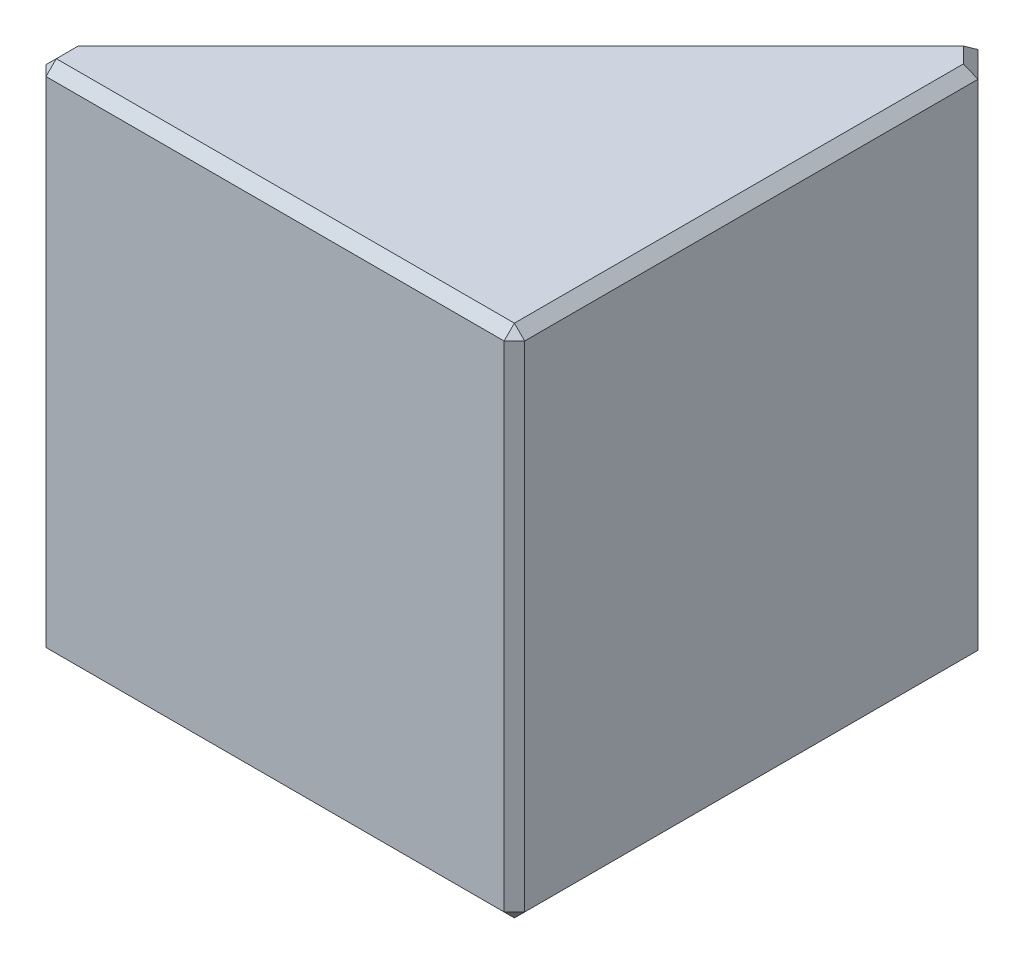
SolidWorks part; units mm, degrees
ref_plane "前视基准面" through (0, 0, 0) normal (0, 0, 1) x (1, 0, 0)
ref_plane "上视基准面" through (0, 0, 0) normal (0, 1, 0) x (1, 0, 0)
ref_plane "右视基准面" through (0, 0, 0) normal (1, 0, 0) x (0, 0, -1)
other "Configuration Table"
sketch "草图1" plane through (0, 0, 0) normal (0, 1, 0) x (1, 0, 0)
  line L0 (0, 0) -> (50, 50)
  line L1 (0, 0) -> (50, 0)
  line L4 (50, 0) -> (50, 50)
  dimension "D1" = 50
  dimension "D2" = 50
extrude "凸台-拉伸1" add sketch "草图1" along normal blind 50
chamfer "倒角1" distance 5 angle 45 2 edges at (50, 25, -50) (0, 25, 0)
chamfer "倒角2" distance 1 angle 45 12 edges at (50, 25, 0) (3.5355, 0, -1.7678) (25.5178, 0, -25.5178) (48.75, 0, -46.25) (50, 0, -22.5) (26.7678, 0, 0) (3.5355, 25, 0) (26.7678, 50, 0) (3.5355, 50, -1.7678) (25.5178, 50, -25.5178) (48.75, 50, -46.25) (50, 50, -22.5)
